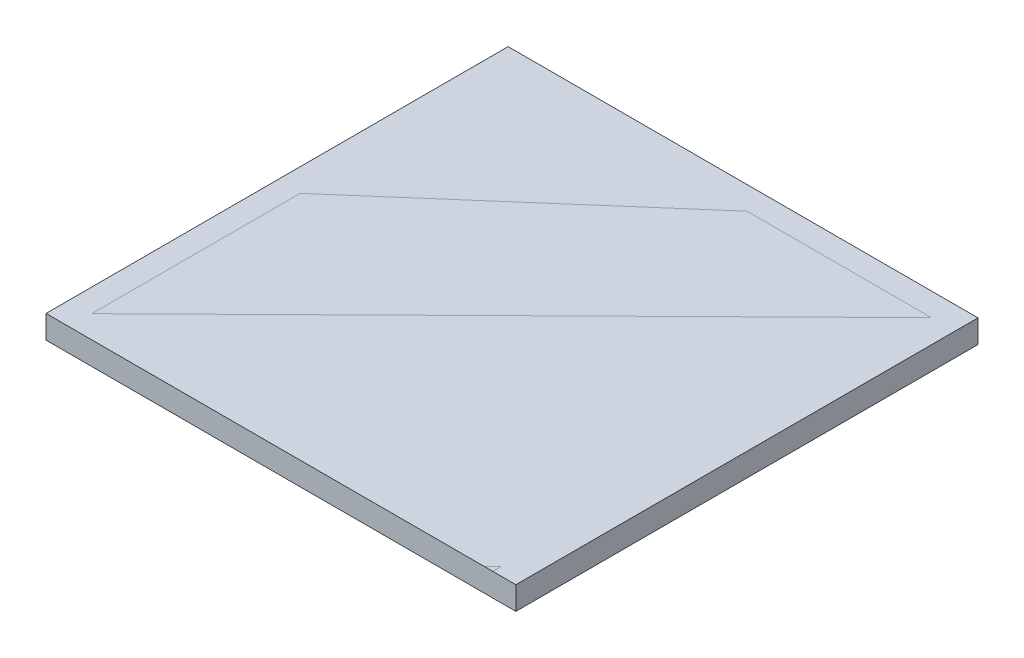
SolidWorks part; units mm, degrees
material "Beech"
ref_plane "Front Plane" through (0, 0, 0) normal (0, 0, 1) x (1, 0, 0)
ref_plane "Top Plane" through (0, 0, 0) normal (0, 1, 0) x (1, 0, 0)
ref_plane "Right Plane" through (0, 0, 0) normal (1, 0, 0) x (0, 0, -1)
sketch "Sketch1" plane through (0, 0, 0) normal (0, 1, 0) x (1, 0, 0)
  line L1 (-30.5, -30) -> (30.5, -30)
  line L2 (-30.5, -30) -> (-30.5, 30)
  line L3 (-30.5, 30) -> (30.5, 30)
  line L4 (30.5, -30) -> (30.5, 30)
  line L5 (-30.5, -30) -> (30.5, 30) construction
  line L6 (-30.5, 30) -> (30.5, -30) construction
  point P0 (0, 0)
  dimension "D1" = 60
  dimension "D2" = 61
extrude "Boss-Extrude1" add sketch "Sketch1" along normal blind 3
sketch "Sketch2" plane through (0, 0, 0) normal (0, -1, 0) x (1, 0, 0)
  line L4 (30.5, -30) -> (30.5, 30)
  line L5 (30.5, 30) -> (-30.5, 30)
  line L6 (-30.5, 30) -> (-30.5, -30)
  line L7 (-30.5, -30) -> (30.5, -30)
  line L8 (30.5, -30) -> (30.5, 30)
  line L9 (30.5, 30) -> (-30.5, 30)
  line L10 (-30.5, 30) -> (-30.5, -30)
  line L11 (-30.5, -30) -> (30.5, -30)
  line L24 (-27.5, 20) -> (-30.5, 20)
  line L25 (-27.5, 30) -> (-27.5, 20)
  line L26 (-27.5, 10) -> (-30.5, 10)
  line L27 (-27.5, 10) -> (-27.5, 0)
  line L28 (-27.5, 0) -> (-30.5, 0)
  line L29 (-27.5, -10) -> (-30.5, -10)
  line L30 (-27.5, -20) -> (-30.5, -20)
  line L31 (-27.5, -10) -> (-27.5, -20)
  line L32 (30.5, -20) -> (27.5, -20)
  line L33 (30.5, -10) -> (27.5, -10)
  line L34 (30.5, 0) -> (27.5, 0)
  line L35 (30.5, 10) -> (27.5, 10)
  line L36 (30.5, 20) -> (27.5, 20)
  line L37 (27.5, 30) -> (27.5, 20)
  line L38 (27.5, 10) -> (27.5, 0)
  line L39 (27.5, -10) -> (27.5, -20)
  line M5 (30.5, -30) -> (30.5, 30)
  line M8 (-30.5, -30) -> (30.5, -30)
  dimension "D1" = 0
extrude "Boss-Extrude2" add sketch "Sketch2" against normal blind 3 separate body contours L39 L33 L34 L38 L35 L36 L37 L9 L25 L24 L10 L26 L27 L28 L29 L31 L30 L32 M5 M8
sketch "Sketch3" plane through (0, 0, 0) normal (0, -1, 0) x (1, 0, 0)
  line L0 (-27.5, -27) -> (27.5, -27)
  line L1 (27.5, -27) -> (27.5, -23)
  line L2 (27.5, -23) -> (24.5, -23)
  line L3 (24.5, -23) -> (24.5, -7)
  line L4 (24.5, -7) -> (27.5, -7)
  line L5 (27.5, -7) -> (27.5, -3)
  line L6 (27.5, -3) -> (24.5, -3)
  line L7 (24.5, -3) -> (24.5, 13)
  line L8 (24.5, 13) -> (27.5, 13)
  line L9 (27.5, 13) -> (27.5, 17)
  line L10 (27.5, 17) -> (24.5, 17)
  line L11 (24.5, 17) -> (24.5, 27)
  line L12 (24.5, 27) -> (-24.5, 27)
  line L13 (-24.5, 27) -> (-24.5, 17)
  line L14 (-24.5, 17) -> (-27.5, 17)
  line L15 (-27.5, 17) -> (-27.5, 13)
  line L16 (-27.5, 13) -> (-24.5, 13)
  line L17 (-24.5, 13) -> (-24.5, -3)
  line L18 (-24.5, -3) -> (-27.5, -3)
  line L19 (-27.5, -3) -> (-27.5, -7)
  line L20 (-27.5, -7) -> (-24.5, -7)
  line L21 (-24.5, -7) -> (-24.5, -23)
  line L22 (-24.5, -23) -> (-27.5, -23)
  line L23 (-27.5, -23) -> (-27.5, -27)
  line L24 (27.5, -20) -> (27.5, -10)
  line L25 (27.5, -10) -> (30.5, -10)
  line L26 (30.5, -10) -> (30.5, 0)
  line L27 (30.5, 0) -> (27.5, 0)
  line L28 (27.5, 0) -> (27.5, 10)
  line L29 (27.5, 10) -> (30.5, 10)
  line L30 (30.5, 10) -> (30.5, 20)
  line L31 (30.5, 20) -> (27.5, 20)
  line L32 (27.5, 20) -> (27.5, 30)
  line L33 (27.5, 30) -> (-27.5, 30)
  line L34 (-27.5, 30) -> (-27.5, 20)
  line L35 (-27.5, 20) -> (-30.5, 20)
  line L36 (-30.5, 20) -> (-30.5, 10)
  line L37 (-30.5, 10) -> (-27.5, 10)
  line L38 (-27.5, 10) -> (-27.5, 0)
  line L39 (-27.5, 0) -> (-30.5, 0)
  line L40 (-30.5, 0) -> (-30.5, -10)
  line L41 (-30.5, -10) -> (-27.5, -10)
  line L42 (-27.5, -10) -> (-27.5, -20)
  line L43 (-27.5, -20) -> (-30.5, -20)
  line L44 (-30.5, -20) -> (-30.5, -30)
  line L45 (-30.5, -30) -> (30.5, -30)
  line L46 (30.5, -30) -> (30.5, -20)
  line L47 (30.5, -20) -> (27.5, -20)
  line L48 (27.5, -20) -> (27.5, -10)
  line L49 (27.5, -10) -> (30.5, -10)
  line L50 (30.5, -10) -> (30.5, 0)
  line L51 (30.5, 0) -> (27.5, 0)
  line L52 (27.5, 0) -> (27.5, 10)
  line L53 (27.5, 10) -> (30.5, 10)
  line L54 (30.5, 10) -> (30.5, 20)
  line L55 (30.5, 20) -> (27.5, 20)
  line L56 (27.5, 20) -> (27.5, 30)
  line L57 (27.5, 30) -> (-27.5, 30)
  line L58 (-27.5, 30) -> (-27.5, 20)
  line L59 (-27.5, 20) -> (-30.5, 20)
  line L60 (-30.5, 20) -> (-30.5, 10)
  line L61 (-30.5, 10) -> (-27.5, 10)
  line L62 (-27.5, 10) -> (-27.5, 0)
  line L63 (-27.5, 0) -> (-30.5, 0)
  line L64 (-30.5, 0) -> (-30.5, -10)
  line L65 (-30.5, -10) -> (-27.5, -10)
  line L66 (-27.5, -10) -> (-27.5, -20)
  line L67 (-27.5, -20) -> (-30.5, -20)
  line L68 (-30.5, -20) -> (-30.5, -30)
  line L69 (-30.5, -30) -> (30.5, -30)
  line L70 (30.5, -30) -> (30.5, -20)
  line L71 (30.5, -20) -> (27.5, -20)
  line L72 (0, 0) -> (0, -53.4866)
  line L73 (30.5, -30) -> (19.5, -30)
  line L74 (30.5, -30) -> (30.5, -27)
  line L75 (30.5, -27) -> (19.5, -27)
  line L76 (19.5, -30) -> (19.5, -27)
  line L77 (-30.5, -30) -> (-19.5, -30)
  line L78 (-30.5, -30) -> (-30.5, -27)
  line L79 (-30.5, -27) -> (-19.5, -27)
  line L80 (-19.5, -30) -> (-19.5, -27)
  line L81 (11.5, -30) -> (3.5, -30)
  line L82 (11.5, -30) -> (11.5, -27)
  line L83 (11.5, -27) -> (3.5, -27)
  line L84 (3.5, -30) -> (3.5, -27)
  line L85 (-11.5, -27) -> (-3.5, -27)
  line L86 (-3.5, -30) -> (-3.5, -27)
  line L87 (-11.5, -30) -> (-3.5, -30)
  line L88 (-11.5, -30) -> (-11.5, -27)
  line M80 (-30.5, -30) -> (30.5, -30)
  line M81 (30.5, -30) -> (30.5, -20)
  dimension "D3" = 11
  dimension "D4" = 11
  dimension "D5" = 8
  dimension "D6" = 8
  dimension "D1" = 0
  dimension "D2" = 3
extrude "Cut-Extrude1" cut sketch "Sketch3" against normal blind 3 contours L76 L75 L0 M80 M81 | L84 L82 L0 M80 | L88 L86 L0 M80 | L80 L0 L79 L68 M80
